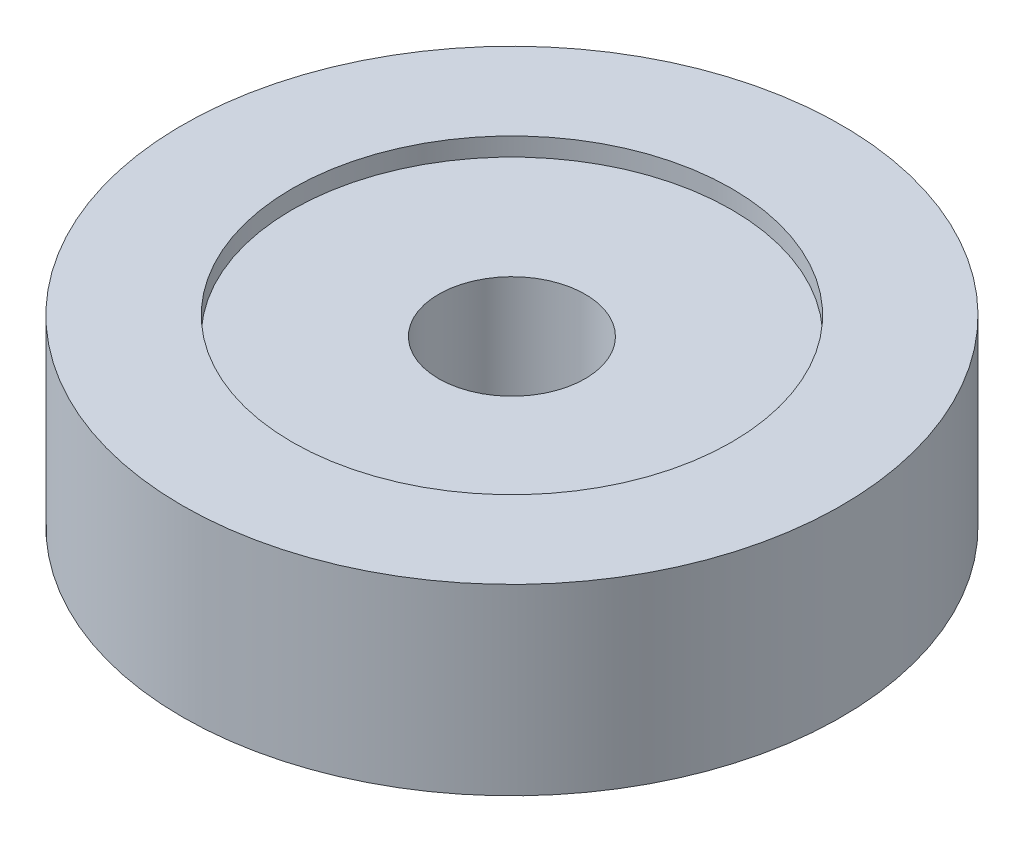
SolidWorks part; units mm, degrees
ref_plane "前视基准面" through (0, 0, 0) normal (0, 0, 1) x (1, 0, 0)
ref_plane "上视基准面" through (0, 0, 0) normal (0, 1, 0) x (1, 0, 0)
ref_plane "右视基准面" through (0, 0, 0) normal (1, 0, 0) x (0, 0, -1)
sketch "草图1" plane through (0, 0, 0) normal (0, 1, 0) x (1, 0, 0)
  circle A0 centre (0, 0) radius 2
  circle A1 centre (0, 0) radius 6
  dimension "D1" = 4
  dimension "D2" = 12
extrude "凸台-拉伸1" add sketch "草图1" along normal mid plane 4
sketch "草图2" plane through (0, 0, 0) normal (0, 1, 0) x (1, 0, 0)
  circle A0 centre (0, 0) radius 9
  circle A1 centre (0, 0) radius 6 construction
  circle A2 centre (0, 0) radius 6
  dimension "D1" = 18
extrude "凸台-拉伸2" add sketch "草图2" along normal mid plane 5 separate body
sketch "草图3" plane through (0, 2.5, 0) normal (0, 1, 0) x (1, 0, 0)
  circle A2 centre (0, 0) radius 8.5
  circle A3 centre (0, 0) radius 8.5 construction
  text T0 "https://item.taobao.com/item.htm?spm=a1z10.3-c.w4002-15226105362.15.e702319dne47Ao&id=538767949710" font "黑体" height 0.5
  dimension "D1" = 0.5
extrude "切除-拉伸1" [suppressed] cut sketch "草图3" against normal blind 0.1
